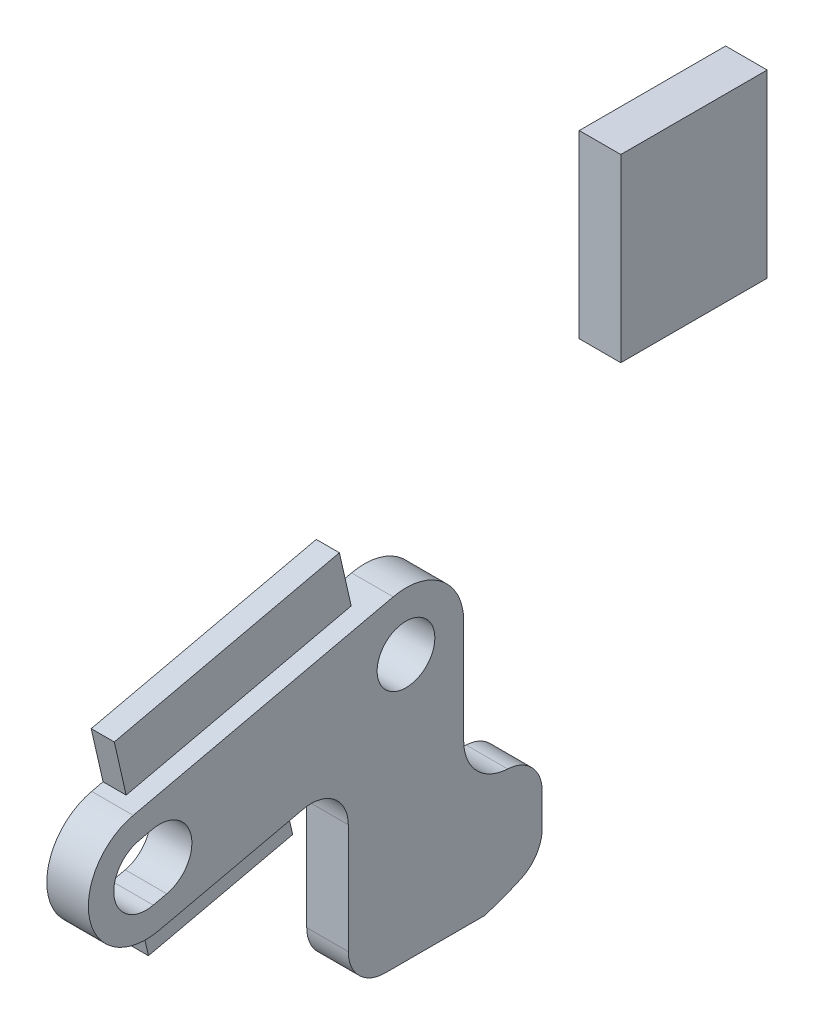
SolidWorks part; units mm, degrees
material "6061-T6 (SS)"
ref_plane "Front Plane" through (0, 0, 0) normal (0, 0, 1) x (1, 0, 0)
ref_plane "Top Plane" through (0, 0, 0) normal (0, 1, 0) x (1, 0, 0)
ref_plane "Right Plane" through (0, 0, 0) normal (1, 0, 0) x (0, 0, -1)
sketch "Sketch1" plane through (0, 0, 0) normal (1, 0, 0) x (0, 0, -1)
  line L0 (-4.318, 27.305) -> (-4.318, 15.875) construction
  line L1 (0, 0) -> (25.4, 0) construction
  line L2 (0, 0) -> (0, 57.989) construction
  line L3 (0, 57.989) -> (25.4, 57.989) construction
  line L4 (25.4, 0) -> (25.4, 57.989) construction
  line L5 (-4.318, 15.875) -> (3.175, 15.875) construction
  line L6 (-18.2459, 24.13) -> (-4.318, 27.305) construction
  line L7 (-1.143, 27.305) -> (-1.143, 19.05)
  line L8 (-18.2459, 30.48) -> (-4.318, 27.305) construction
  line L9 (-1.143, 19.05) -> (3.175, 19.05)
  line L10 (3.175, 19.05) -> (3.175, 15.875)
  line L11 (3.175, 12.7) -> (-7.493, 12.7)
  line L12 (-7.493, 12.7) -> (-7.493, 27.305)
  line L13 (-0.508, 36.4075) -> (-0.508, -6.1063) construction
  line L14 (-4.318, 27.305) -> (-9.2717, 17.0043) construction
  line L15 (-9.2717, 17.0043) -> (-2.519, 13.7568) construction
  line L16 (-18.2459, 30.48) -> (-18.2459, 24.13) construction
  line L17 (3.175, 15.875) -> (3.175, 12.7)
  line L18 (-7.493, 19.05) -> (-4.318, 19.05) construction
  line L19 (-4.318, 19.05) -> (-1.143, 19.05) construction
  line L20 (-1.143, 16.6181) -> (-2.519, 13.7568) construction
  line L21 (-3.6123, 24.2094) -> (-17.9117, 20.9497)
  line L22 (-19.323, 27.1409) -> (-5.0237, 30.4006)
  line L29 (-18.6173, 24.0453) -> (-17.8744, 24.2147) construction
  line L32 (-19.0125, 25.7788) -> (-18.2696, 25.9482)
  line L33 (-18.2221, 22.3118) -> (-17.4792, 22.4812)
  line L34 (-18.6173, 30.5647) -> (-17.8744, 30.3953) construction
  line L35 (-18.2221, 32.2982) -> (-17.4792, 32.1288)
  line L36 (-19.0125, 28.8312) -> (-18.2696, 28.6618)
  line L37 (-17.8744, 30.3953) -> (-18.2459, 30.48) construction
  line L39 (-1.143, 19.05) -> (-1.143, -6.5422) construction
  line L40 (-17.8744, 24.2147) -> (-18.2459, 24.13) construction
  line L41 (-4.318, 27.305) -> (-18.2459, 27.305) construction
  circle A0 centre (-4.318, 27.305) radius 3.175
  circle A1 centre (-4.318, 27.305) radius 1.5875
  circle A8 centre (-18.6173, 24.0453) radius 3.175
  arc A9 (-19.0125, 25.7788) -> (-18.2221, 22.3118) centre (-18.6173, 24.0453) ccw
  arc A10 (-17.4792, 22.4812) -> (-18.2696, 25.9482) centre (-17.8744, 24.2147) ccw
  arc A11 (-18.2221, 32.2982) -> (-19.0125, 28.8312) centre (-18.6173, 30.5647) ccw
  arc A12 (-18.2696, 28.6618) -> (-17.4792, 32.1288) centre (-17.8744, 30.3953) ccw
  point P30 (-18.2459, 24.13)
  point P40 (-18.2459, 30.48)
  dimension "D2" = 6.35
  dimension "D4" = 3.175
  dimension "D14" = 6.35
  dimension "D12" = 1.778
  dimension "D1" = 25.4
  dimension "D3" = 3.175
  dimension "D5" = 15.875
  dimension "D9" = 11.43
  dimension "D10" = 25.683
  dimension "D6" = 0.508
  dimension "D13" = 0.762
  dimension "D8" = 25.683
  dimension "D7" = 6.35
  dimension "D11" = 0.635
sketch "Sketch2" plane through (0, 0, 0) normal (1, 0, 0) x (0, 0, -1)
  line L0 (-19.323, 27.1409) -> (-5.0237, 30.4006) construction
  line L1 (-19.323, 27.1409) -> (-5.0237, 30.4006)
  line L2 (-3.6123, 24.2094) -> (-17.9117, 20.9497) construction
  line L3 (-7.493, 23.3248) -> (-17.9117, 20.9497)
  line L4 (-1.143, 27.305) -> (-1.143, 19.05) construction
  line L5 (-1.143, 27.305) -> (-1.143, 19.05)
  line L6 (-7.493, 12.7) -> (-7.493, 27.305) construction
  line L7 (-7.493, 12.7) -> (-7.493, 23.3248)
  line L8 (3.175, 12.7) -> (-7.493, 12.7) construction
  line L9 (3.175, 12.7) -> (-7.493, 12.7)
  line L10 (-1.143, 19.05) -> (3.175, 19.05) construction
  line L11 (-1.143, 19.05) -> (3.175, 19.05)
  line L12 (3.175, 19.05) -> (3.175, 15.875) construction
  line L13 (3.175, 19.05) -> (3.175, 15.875)
  line L14 (3.175, 15.875) -> (3.175, 12.7) construction
  line L15 (3.175, 15.875) -> (3.175, 12.7)
  line L21 (-18.2221, 22.3118) -> (-17.4792, 22.4812) construction
  line L22 (-19.0125, 25.7788) -> (-18.2696, 25.9482) construction
  line L23 (-18.2221, 22.3118) -> (-17.4792, 22.4812)
  line L24 (-19.0125, 25.7788) -> (-18.2696, 25.9482)
  circle A2 centre (-4.318, 27.305) radius 3.175 construction
  arc A3 (-1.143, 27.305) -> (-5.0237, 30.4006) centre (-4.318, 27.305) ccw
  circle A4 centre (-4.318, 27.305) radius 1.5875 construction
  circle A5 centre (-4.318, 27.305) radius 1.5875
  circle A7 centre (-18.6173, 24.0453) radius 3.175 construction
  arc A8 (-19.323, 27.1409) -> (-17.9117, 20.9497) centre (-18.6173, 24.0453) ccw
  arc A15 (-19.0125, 25.7788) -> (-18.2221, 22.3118) centre (-18.6173, 24.0453) ccw construction
  arc A16 (-17.4792, 22.4812) -> (-18.2696, 25.9482) centre (-17.8744, 24.2147) ccw construction
  arc A17 (-19.0125, 25.7788) -> (-18.2221, 22.3118) centre (-18.6173, 24.0453) ccw
  arc A18 (-17.4792, 22.4812) -> (-18.2696, 25.9482) centre (-17.8744, 24.2147) ccw
extrude "Boss-Extrude1" add sketch "Sketch2" along normal blind 2.286
fillet "Fillet1" radius 2.032 2 edges at (1.143, 23.3248, 7.493) (1.143, 12.7, 7.493)
fillet "Fillet3" radius 2.54 1 edges at (1.143, 19.05, 1.143)
sketch "Sketch4" plane through (2.286, 0, 0) normal (1, 0, 0) x (0, 0, -1)
  line L7 (3.175, 14.0458) -> (3.175, 12.7)
  line L8 (3.175, 12.7) -> (3.175, 19.05) construction
  line L9 (3.175, 12.7) -> (0, 12.7)
  arc A0 (0, 12.7) -> (3.175, 14.0458) centre (-4.318, 27.305) ccw
  dimension "D1" = 3.175
extrude "Cut-Extrude2" cut sketch "Sketch4" against normal through all
fillet "Fillet4" radius 2 1 edges at (1.143, 14.0458, -3.175)
fillet "Fillet5" radius 2 1 edges at (1.143, 19.05, -3.175)
sketch "Sketch5" plane through (0, 0, 0) normal (-1, 0, 0) x (0, 0, 1)
  line L0 (6.3153, 30.1061) -> (18.6977, 27.2835)
  line L1 (6.3153, 30.1061) -> (6.9673, 32.9661)
  line L2 (18.6977, 27.2835) -> (19.3496, 30.1434)
  line L3 (6.9673, 32.9661) -> (19.3496, 30.1434)
  line L4 (5.0237, 30.4006) -> (19.323, 27.1409) construction
  line L27 (9.9766, 22.7586) -> (17.9117, 20.9497)
  line L32 (9.9766, 22.7586) -> (9.536, 20.8255)
  line L33 (17.9117, 20.9497) -> (17.471, 19.0166)
  line L34 (9.536, 20.8255) -> (17.471, 19.0166)
  dimension "D1" = 12.7
extrude "Boss-Extrude2" add sketch "Sketch5" against normal blind 1.27
sketch "Sketch6" plane through (2.286, 0, 0) normal (1, 0, 0) x (0, 0, -1)
  line L1 (7.4988, 45.2138) -> (15.5523, 45.2138)
  line L2 (7.4988, 45.2138) -> (7.4988, 35.2928)
  line L3 (7.4988, 35.2928) -> (15.5523, 35.2928)
  line L4 (15.5523, 45.2138) -> (15.5523, 35.2928)
extrude "Boss-Extrude3" add sketch "Sketch6" against normal up to surface (2.286 mm away) separate body up to face at (0, 27.305, 2.7305)
equation "\"D8@Sketch1\"=\"D10@Sketch1\""
